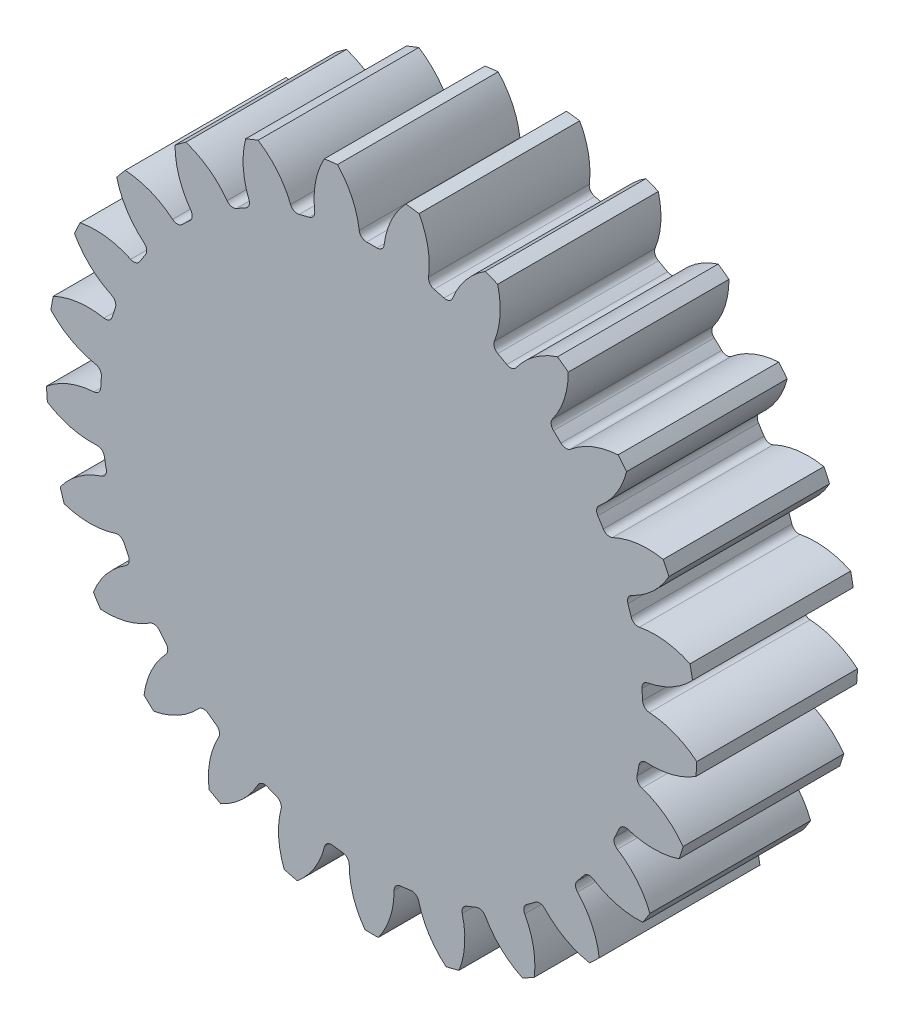
SolidWorks part; units mm, degrees
material "6061-T6 (SS)"
ref_plane "Front Plane" through (0, 0, 0) normal (0, 0, 1) x (1, 0, 0)
ref_plane "Top Plane" through (0, 0, 0) normal (0, 1, 0) x (1, 0, 0)
ref_plane "Right Plane" through (0, 0, 0) normal (1, 0, 0) x (0, 0, -1)
sketch "Sketch1" plane through (0, 0, 0) normal (0, 0, 1) x (1, 0, 0)
  circle A0 centre (0, 0) radius 37.5
  circle A1 centre (0, 0) radius 40.5
  circle A2 centre (0, 0) radius 33.75
  dimension "D1" = 75
  dimension "D2" = 81
  dimension "D3" = 6.75
extrude "Boss-Extrude1" add sketch "Sketch1" along normal mid plane 20 contours A1
sketch "Sketch2" plane through (0, 0, 0) normal (0, 0, 1) x (1, 0, 0)
  line L0 (0, 0) -> (0, 40.5) construction
  line L1 (-2.3546, 37.426) -> (2.3546, 37.426) construction
  line L2 (-1.4809, 33.7175) -> (0, 0) construction
  line L3 (0, 32.1374) -> (-4.079, 41.299) construction
  line L4 (0, 0) -> (5.076, 40.1806) construction
  line L5 (2.3546, 37.426) -> (7.0268, 36.8358) construction
  circle A0 centre (0, 0) radius 40.5 construction
  arc A1 (-5.2103, 41.1716) -> (-1.4809, 33.7175) centre (-11.6913, 33.269) cw
  arc A2 (5.2103, 41.1716) -> (1.4809, 33.7175) centre (11.6913, 33.269) ccw
  circle A3 centre (0, 0) radius 33.75 construction
  arc A4 (1.4809, 33.7175) -> (-1.4809, 33.7175) centre (0, 0) ccw
  circle A6 centre (0, 0) radius 37.5 construction
  circle A7 centre (0, 0) radius 41.5
  arc A8 (5.2103, 41.1716) -> (-5.2103, 41.1716) centre (0, 0) ccw
  circle A9 centre (0, 0) radius 40.5 construction
  point P19 (1.4722, 33.7179)
  point P26 (7.3421, 36.7742)
  dimension "D2" = 24
  dimension "D3" = 7.2
  dimension "D1" = 1
extrude "Cut-Extrude1" cut sketch "Sketch2" against normal through all both and the other way through all
fillet "Fillet1" radius 0.9 2 edges at (1.4809, 33.7175, 0) (-1.4809, 33.7175, 0)
pattern_circular "CirPattern1" count 25 over 360 about axis through (0, 0, 0) along (0, 0, 1) of "Cut-Extrude1", "Fillet1"
equation "\"Module\"= 3mm"
equation "\"Number of Teeth\"= 25"
equation "\"D1@Sketch1\"=\"Module\" * \"Number of Teeth\""
equation "\"D2@Sketch1\"=(\"Number of Teeth\" + 2) * \"Module\""
equation "\"D3@Sketch1\"=\"Module\" * if( \"Module\"=>1.25,2.25,2.4)"
equation "\"Pressure Angle\"= 24deg"
equation "\"D2@Sketch2\"=\"Pressure Angle\""
equation "\"D3@Sketch2\"=180 / \"Number of Teeth\""
equation "\"D1@Fillet1\"=0.3 * \"Module\""
equation "\"D1@CirPattern1\"=\"Number of Teeth\""
